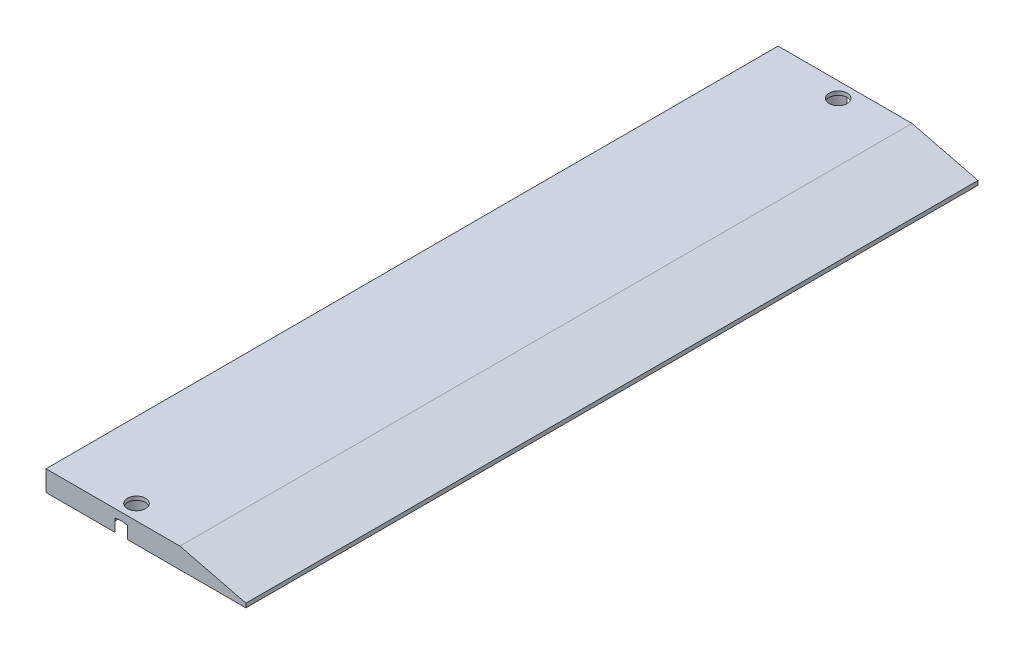
SolidWorks part; units mm, degrees
material "40Х13 ГОСТ 4543-71"
ref_plane "Спереди" through (0, 0, 0) normal (0, 0, 1) x (1, 0, 0)
ref_plane "Сверху" through (0, 0, 0) normal (0, 1, 0) x (1, 0, 0)
ref_plane "Справа" through (0, 0, 0) normal (1, 0, 0) x (0, 0, -1)
sketch "Sketch1" plane through (0, 0, 0) normal (0, 0, 1) x (1, 0, 0)
  line L0 (0, 0) -> (0, 2.5)
  line L1 (0, 2.5) -> (16.2784, 2.5)
  line L2 (16.2784, 2.5) -> (24.3, 0.5)
  line L3 (24.3, 0) -> (0, 0)
  line L4 (24.3, 0.5) -> (24.3, 0)
  point P5 (24.0045, 0.5)
  point P6 (24.8517, 0.5)
  dimension "D1" = 2.5
  dimension "D2" = 166
  dimension "D3" = 0.5
  dimension "D4" = 16.2784
  dimension "D5" = 24.3
extrude "Boss-Extrude1" add sketch "Sketch1" along normal mid plane 89
sketch "Sketch4" plane through (0, 0, 0) normal (0, -1, 0) x (1, 0, 0)
  line L0 (0, 44.5) -> (0, -44.5) construction
  point P0 (9.15, 42.65)
  point P1 (9.15, -42.65)
  dimension "D1" = 85.3
  dimension "D2" = 42.65
  dimension "D3" = 9.15
hole_wizard "HoleWzd2" positions "3DSketch3" profile "Sketch6" legacy end condition up to next
sketch3d "3DSketch3"
  point P0 (9.15, 0, 42.65)
  point P3 (9.15, 0, -42.65)
sketch "Sketch6" plane through (9.15, 0, 42.65) normal (1, 0, 0) x (0, 0, -1)
  line L0 (0, 0) -> (0, 2.5)
  line L1 (0, 2.5) -> (1.1, 2.5)
  line L2 (1.1, 2.5) -> (1.1, 2.0408)
  line L3 (1.1, 2.0408) -> (2, 1.5)
  line L4 (2, 1.5) -> (2, 0)
  line L5 (2, 0) -> (0, 0)
  line L6 (0, -6.13) -> (0, 109.2824) construction
  line L7 (-1.1, 2.0408) -> (-2, 1.5) construction
  line L8 (0, 2.5) -> (-1.1, 2.5) construction
  dimension "Diameter" = 2.2
  dimension "Depth" = 2.5
  dimension "C-Drill Diameter" = 4
  dimension "C-Drill Depth" = 1.5
  dimension "C-Drill Angle" = 118
equation "\"dist_hole\"= 83 + 2.3"
